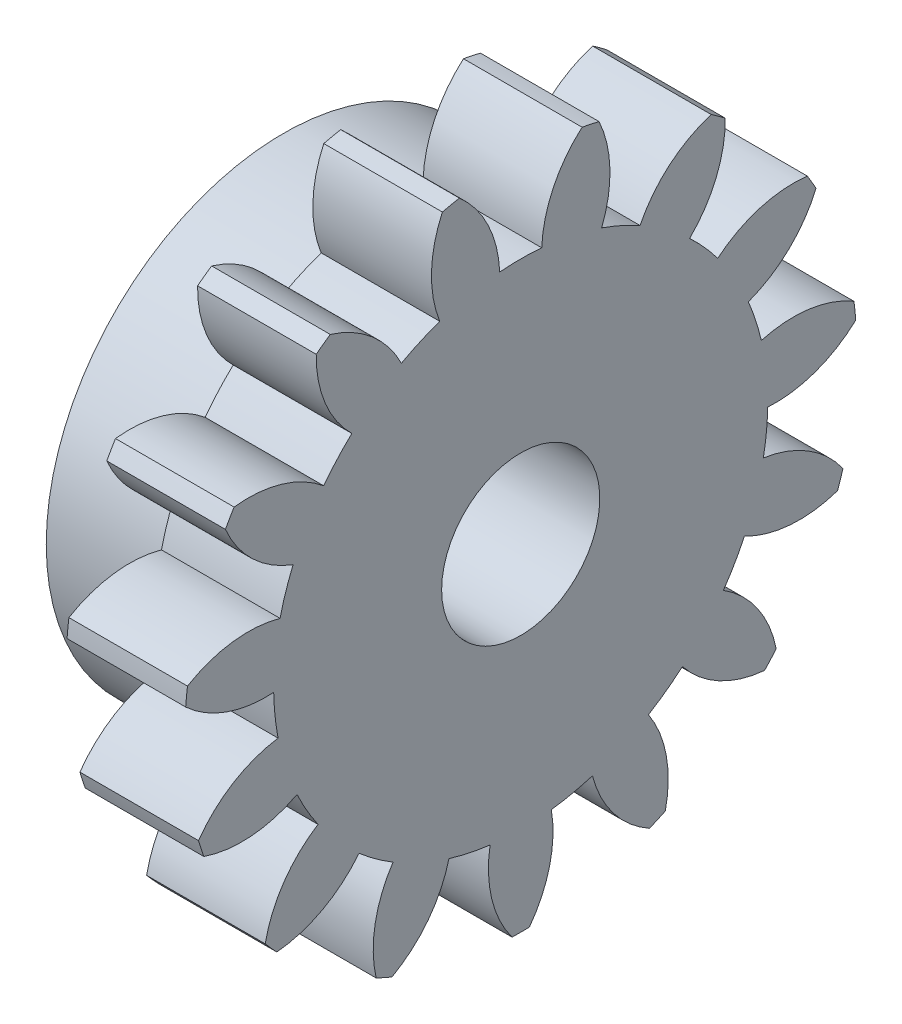
SolidWorks part; units mm, degrees
ref_plane "Plane1" through (0, 0, 0) normal (0, 0, 1) x (1, 0, 0)
ref_plane "Plane2" through (0, 0, 0) normal (0, 1, 0) x (1, 0, 0)
ref_plane "Plane3" through (0, 0, 0) normal (1, 0, 0) x (0, 0, -1)
sketch "HoldingSke" plane through (0, 0, 0) normal (0, 1, 0) x (1, 0, 0)
  line L0 (0, 0) -> (0.9659, -0.2588)
  line L1 (-15, 0) -> (100, 0) construction
  line L2 (0, 0) -> (-2.1039, 2.3779)
  line L3 (0, 0) -> (-11.863, 4.5341)
  line L4 (0, 0) -> (8.3417, 2.2352)
  line L5 (0, 0) -> (-5.6217, -2.0967)
  line L6 (0, 0) -> (-2.4869, -1.6779)
  line L7 (-2.1039, 2.3779) -> (-0.8124, 8.2373)
  line L8 (-76.2, 54.61) -> (-75.5, 54.61)
  line L9 (-71.009, 38.7566) -> (-53.1078, 45.2721)
  line L10 (-76.2, 71.12) -> (104.1128, 71.12)
  line L11 (0, 0) -> (-3, 0)
  line L12 (-76.2, 101.6) -> (-76.162, 101.6)
  line L13 (24.9733, 27.94) -> (52.9518, 28.4284)
  line L14 (24.9733, 27.94) -> (24.9743, 27.94)
  line L15 (24.9733, 27.94) -> (100.4006, 29.5858)
  line L16 (-63.627, -1) -> (-12.827, -1)
  circle A0 centre (0, 0) radius 2
  circle A1 centre (0, 0) radius 6
  circle A2 centre (0, 0) radius 6
  circle A3 centre (0, 0) radius 2
  dimension "MHD" = 12
  dimension "Hub_dia" = 12
  dimension "Bore" = 4
  dimension "MBD" = 4
  dimension "Num_teeth" = 15
  dimension "Pitch" = 1
  dimension "Overall_len" = 6
  dimension "Show_teeth" = 15
  dimension "Thickness" = 3
  dimension "OAL" = 6.0001
  dimension "T_dim" = 0.7
  dimension "Ap" = 20
  dimension "H" = 19.05
  dimension "Pitch_radius" = 180.3128
  dimension "Width" = 3
  dimension "Backlash" = 0.038
  dimension "Addendum_fac" = 1
  dimension "Dedendum_fac" = 1.25
  dimension "Clearance_fac" = 0.25
  dimension "Dedendum_add" = 0.001
  dimension "Module" = 1
sketch "BasProSke" plane through (0, 0, 0) normal (0, 1, 0) x (1, 0, 0)
  line L0 (-10, 0) -> (60, 0) construction
  line L1 (0, 0) -> (0, 8.5)
  line L2 (0, 0) -> (3, 0)
  line L3 (3, 0) -> (3, 8.5)
  line L4 (3, 8.5) -> (0, 8.5)
  dimension "Thickness" = 3
  dimension "Diameter" = 17
revolve "Base-Revolve" add sketch "BasProSke" angle 360 about L0
sketch "TooCutSke" plane through (0, 0, 0) normal (1, 0, 0) x (0, 0, -1)
  line L1 (0, 0) -> (0, 107) construction
  line L2 (0, 0) -> (-0.8504, 7.4516) construction
  line L3 (0, 0) -> (-3.1044, 14.6049) construction
  line L4 (-0.8504, 7.4516) -> (-1.5522, 7.3025) construction
  arc A0 (0.5316, 6.2263) -> (-0.5316, 6.2263) centre (0, 0) ccw
  arc A1 (1.5766, 8.3784) -> (-1.5766, 8.3784) centre (0, 0) ccw
  circle A2 centre (0, 0) radius 7.5 construction
  circle A3 centre (0, 0) radius 7.0477 construction
  arc A4 (-0.5316, 6.2263) -> (-1.5766, 8.3784) centre (-3.5289, 6.1005) ccw
  arc A5 (1.5766, 8.3784) -> (0.5316, 6.2263) centre (3.5289, 6.1005) ccw
  dimension "Root_dia" = 12.498
  dimension "Overcut_dia" = 17.0508
  dimension "Pitch_dia" = 15
  dimension "Base_dia" = 14.0954
  dimension "Flank_rad" = 3
  dimension "Half_ang" = 12
  dimension "Half_CT" = 0.7175
extrude "ToothCut" cut sketch "TooCutSke" along normal through all
fillet "Breaks" [suppressed] radius 0.02
fillet "RootFillets" [suppressed] radius 0.251
pattern_circular "TeethCuts" count 15 every 24 about axis through (-10, 0, 0) along (1, 0, 0) of "ToothCut", "RootFillets", "Breaks"
sketch "HubNeaOneSke" plane through (0, 0, 0) normal (-1, 0, 0) x (0, 0, 1)
  circle A0 centre (0, 0) radius 6
  dimension "Diameter" = 12
extrude "HubNearOne" add sketch "HubNeaOneSke" along normal blind 3.0001
sketch "HubNeaBotSke" plane through (0, 0, 0) normal (-1, 0, 0) x (0, 0, 1)
  circle A0 centre (0, 0) radius 6
  dimension "Diameter" = 12
extrude "HubNearBoth" [suppressed] add sketch "HubNeaBotSke" along normal blind 1.5
ref_plane "FarPln" through (3, 0, 0) normal (1, 0, 0) x (0, 0, -1)
sketch "HubFarSke" plane through (3, 0, 0) normal (1, 0, 0) x (0, 0, -1)
  circle A0 centre (0, 0) radius 6
  dimension "Diameter" = 12
extrude "HubFar" [suppressed] add sketch "HubFarSke" along normal blind 1.5
sketch "BorSke" plane through (0, 0, 0) normal (1, 0, 0) x (0, 0, -1)
  circle A0 centre (0, 0) radius 2
  dimension "Diameter" = 4
extrude "Bore" cut sketch "BorSke" along normal mid plane 12.0001
sketch "KeySke" plane through (0, 0, 0) normal (1, 0, 0) x (0, 0, -1)
  line L0 (-0.8, 0) -> (-0.8, 2.7)
  line L1 (-0.8, 2.7) -> (0.8, 2.7)
  line L2 (0.8, 2.7) -> (0.8, 0)
  line L3 (0, 0) -> (0, 34) construction
  line L4 (-0.8, 0) -> (0.8, 0)
  dimension "Offset" = 2.7
  dimension "Width" = 1.6
extrude "Keyway" [suppressed] cut sketch "KeySke" along normal mid plane 12.0001
pattern_circular "Keyway2" [suppressed] count 2 every 90 about axis through (-10, 0, 0) along (1, 0, 0)
equation "' \"Module@HoldingSke\" = 6.35"
equation "' \"Num_teeth@HoldingSke\" = 12"
equation "' \"Ap@HoldingSke\" =  20"
equation "' \"Ap@HoldingSke\" = 20"
equation "' \"Width@HoldingSke\" = 0.5 * 25.4"
equation "' \"Hub_dia@HoldingSke\"= 1 * 25.4"
equation "' \"Hub_dia@HoldingSke\" = 1 * 25.4"
equation "' \"Overall_len@HoldingSke\" = 1.0 * 25.4"
equation "' \"Bore@HoldingSke\" = 0.75 * 25.4"
equation "' \"T_dim@HoldingSke\" = 0.1 * 25.4"
equation "' \"Width@KeySke\" = 0.25 * 25.4"
equation "' \"Show_teeth@HoldingSke\" = 13"
equation "' \"Backlash@HoldingSke\" = 0.009 * 25.4"
equation "' \"Addendum_fac@HoldingSke\" = 1.0"
equation "' \"Dedendum_fac@HoldingSke\" = 1.25"
equation "' \"Dedendum_add@HoldingSke\" = 0.00005 * 25.4"
equation "' \"Clearance_fac@HoldingSke\" = 0.25"
equation "\"Pitch@HoldingSke\" = 1 / \"Module@HoldingSke\""
equation "\"Overcut_dia@TooCutSke\" = (\"Num_teeth@HoldingSke\" + 2 * \"Addendum_fac@HoldingSke\") / \"Pitch@HoldingSke\" + 0.002 * 25.4"
equation "\"Pitch_dia@TooCutSke\" = \"Num_teeth@HoldingSke\" / \"Pitch@HoldingSke\""
equation "\"Base_dia@TooCutSke\" = \"Num_teeth@HoldingSke\" / \"Pitch@HoldingSke\" * cos((\"Ap@HoldingSke\"  * 3.14159265 / 180))"
equation "\"Root_dia@TooCutSke\" = (\"Num_teeth@HoldingSke\" + 2) / \"Pitch@HoldingSke\" - 2 * (\"Addendum_fac@HoldingSke\" + \"Dedendum_fac@HoldingSke\") / \"Pitch@HoldingSke\" - \"Dedendum_add@HoldingSke\" * 2"
equation "\"Half_ang@TooCutSke\" = 180 / \"Num_teeth@HoldingSke\""
equation "\"Half_CT@TooCutSke\" = \"Num_teeth@HoldingSke\" / \"Pitch@HoldingSke\" * sin((3.14159265 / 2 / \"Num_teeth@HoldingSke\")) / 2 - 7 * \"Backlash@HoldingSke\" / 4"
equation "\"Flank_rad@TooCutSke\" = \"Num_teeth@HoldingSke\" / \"Pitch@HoldingSke\" / 5"
equation "\"Radius@RootFillets\" = \"Clearance_fac@HoldingSke\" / \"Pitch@HoldingSke\" + \"Dedendum_add@HoldingSke\""
equation "\"Break_rad@Breaks\" = 0.02 / \"Pitch@HoldingSke\""
equation "\"Thickness@HoldingSke\" = \"Width@HoldingSke\""
equation "\"OAL@HoldingSke\" = \"Thickness@HoldingSke\""
equation "\"MHD@HoldingSke\" = (\"Num_teeth@HoldingSke\" + 2) / \"Pitch@HoldingSke\" - 2 * (\"Addendum_fac@HoldingSke\" + \"Dedendum_fac@HoldingSke\")  / \"Pitch@HoldingSke\" - \"Dedendum_add@HoldingSke\" * 2"
equation "\"MBD@HoldingSke\" = (\"Num_teeth@HoldingSke\" + 2) / \"Pitch@HoldingSke\" - 2 * (\"Addendum_fac@HoldingSke\" + \"Dedendum_fac@HoldingSke\")  / \"Pitch@HoldingSke\" - \"Dedendum_add@HoldingSke\" * 2 - 0.002 * 25.4"
equation "\"MHD@HoldingSke\" = ((sgn( \"MHD@HoldingSke\" - \"Hub_dia@HoldingSke\" )-1)*( \"MHD@HoldingSke\" - \"Hub_dia@HoldingSke\" ))/-2+ \"Hub_dia@HoldingSke\""
equation "\"MBD@HoldingSke\" = ((sgn( \"MBD@HoldingSke\" - \"Bore@HoldingSke\" )-1)*( \"MBD@HoldingSke\" - \"Bore@HoldingSke\" ))/-2+ \"Bore@HoldingSke\""
equation "\"OAL@HoldingSke\" = ((sgn( \"OAL@HoldingSke\" - \"Overall_len@HoldingSke\" )+1)*( \"OAL@HoldingSke\" - \"Overall_len@HoldingSke\" ))/2 + \"Overall_len@HoldingSke\" + 0.000002 * 25.4"
equation "\"Num_teeth@TeethCuts\" = int( \"Show_teeth@HoldingSke\" ) + 1"
equation "\"Num_teeth@TeethCuts\" = ((sgn( \"Num_teeth@TeethCuts\" - \"Num_teeth@HoldingSke\" )-1)*( \"Num_teeth@TeethCuts\" - \"Num_teeth@HoldingSke\" ))/-2+ \"Num_teeth@HoldingSke\""
equation "\"Num_teeth@TeethCuts\" = ((sgn( \"Num_teeth@TeethCuts\" - 2.0)+1)*( \"Num_teeth@TeethCuts\" - 2.0))/2 +2.0"
equation "\"Angle@TeethCuts\" = 360.0 / \"Num_teeth@HoldingSke\""
equation "\"Diameter@BasProSke\" = (\"Num_teeth@HoldingSke\" + 2 * \"Addendum_fac@HoldingSke\") / \"Pitch@HoldingSke\""
equation "\"Thickness@BasProSke\"  = \"Thickness@HoldingSke\""
equation "' \"Fillet_rad@BasProSke\" =  \"Thickness@HoldingSke\" * 0.05"
equation "' \"Fillet_rad@BasProSke\" = \"Thickness@HoldingSke\" * 0.05"
equation "\"MHD@HoldingSke\" = ((sgn( \"MHD@HoldingSke\" - \"Root_dia@TooCutSke\" )-1)*( \"MHD@HoldingSke\" - \"Root_dia@TooCutSke\" ))/-2+ \"Root_dia@TooCutSke\""
equation "\"Diameter@HubNeaOneSke\" = \"MHD@HoldingSke\""
equation "\"Length@HubNearOne\" = \"OAL@HoldingSke\" - \"Thickness@BasProSke\""
equation "\"Diameter@HubNeaBotSke\" = \"MHD@HoldingSke\""
equation "\"Length@HubNearBoth\" = ( \"OAL@HoldingSke\" - \"Thickness@BasProSke\" ) / 2.0"
equation "\"Thickness@FarPln\" = \"Thickness@BasProSke\""
equation "\"Diameter@HubFarSke\" = \"MHD@HoldingSke\""
equation "\"Length@HubFar\" = ( \"OAL@HoldingSke\" - \"Thickness@BasProSke\" ) / 2.0"
equation "\"Diameter@BorSke\" = \"MBD@HoldingSke\""
equation "\"D1@Bore\" = \"OAL@HoldingSke\" * 2.0"
equation "\"D1@Keyway\" = \"OAL@HoldingSke\" * 2.0"
equation "\"Offset@KeySke\" = \"T_dim@HoldingSke\" + \"MBD@HoldingSke\" / 2.0"
